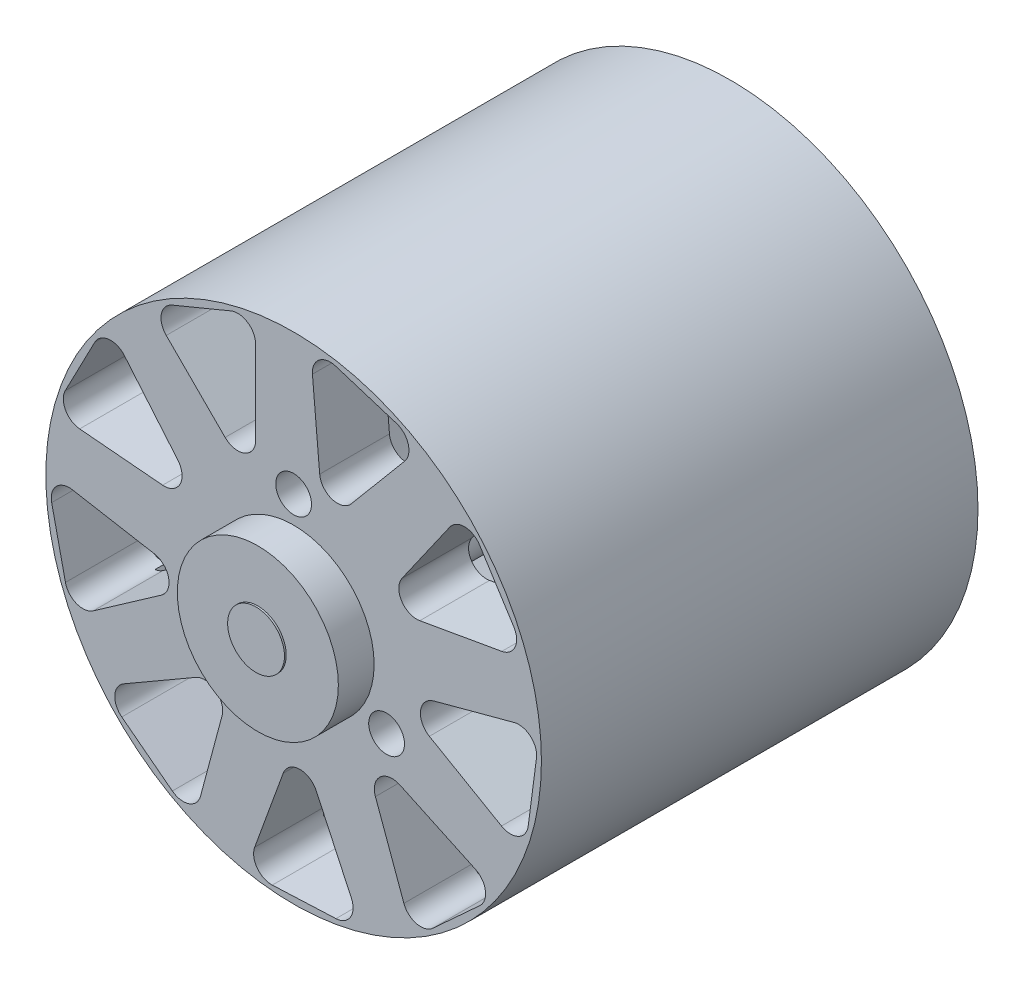
SolidWorks part; units mm, degrees
ref_plane "Front Plane" through (0, 0, 0) normal (0, 0, 1) x (1, 0, 0)
ref_plane "Top Plane" through (0, 0, 0) normal (0, 1, 0) x (1, 0, 0)
ref_plane "Right Plane" through (0, 0, 0) normal (1, 0, 0) x (0, 0, -1)
sketch "Sketch1" plane through (0, 0, 0) normal (0, 0, 1) x (1, 0, 0)
  circle A0 centre (0, 0) radius 13.85
  dimension "D1" = 27.7
extrude "Boss-Extrude1" add sketch "Sketch1" along normal blind 24.4
sketch "Sketch2" plane through (0, 0, 0) normal (0, 0, -1) x (-1, 0, 0)
  circle A0 centre (0, 0) radius 12.85
  dimension "D1" = 25.7
extrude "Cut-Extrude1" cut sketch "Sketch2" against normal blind 20.5
ref_plane "Plane1" through (0, 0, 24.4) normal (0, 0, 1) x (1, 0, 0)
sketch "Sketch3" plane through (0, 0, 24.4) normal (0, 0, 1) x (1, 0, 0)
  line L0 (0, 0) -> (0, 6) construction
  line L1 (0, 0) -> (4.2426, 4.2426) construction
  line L2 (0, 6) -> (4.2426, 4.2426) construction
  line L3 (0, 0) -> (-4.2426, 4.2426) construction
  line L4 (-4.2426, 4.2426) -> (0, 6) construction
  line L5 (1.4565, 7.6917) -> (1.0508, 12.3285)
  line L6 (-2.1213, 7.5355) -> (-2.1213, 12.19)
  line L7 (-3.8284, 6.8284) -> (-7.1196, 10.1196)
  line L8 (-6.7952, 11.7506) -> (-3.504, 13.1139)
  line L9 (2.3477, 13.3693) -> (5.7452, 12.2981)
  line L10 (3.2187, 7.1361) -> (6.2105, 10.7016)
  line L11 (6.0599, 4.956) -> (8.7296, 8.7687)
  line L12 (10.3921, 8.7324) -> (12.3062, 5.728)
  line L13 (7.0527, 3.3976) -> (11.6364, 4.2059)
  line L14 (7.8278, -0.0987) -> (12.3237, 1.106)
  line L15 (13.5739, 0.0095) -> (13.1089, -3.5224)
  line L16 (7.5866, -1.9306) -> (11.6175, -4.2579)
  line L17 (5.933, -5.1072) -> (10.1514, -7.0743)
  line L18 (10.4043, -8.7179) -> (7.7779, -11.1246)
  line L19 (4.5707, -6.3556) -> (6.1626, -10.7293)
  line L20 (1.2621, -7.726) -> (3.2291, -11.9444)
  line L21 (2.3664, -13.366) -> (-1.1925, -13.5214)
  line L22 (-0.5839, -7.8066) -> (-2.1758, -12.1804)
  line L23 (-3.9994, -6.7297) -> (-5.204, -11.2256)
  line L24 (-6.7787, -11.7601) -> (-9.6049, -9.5915)
  line L25 (-5.4653, -5.6049) -> (-9.4962, -7.9321)
  line L26 (-7.3895, -2.5845) -> (-11.2022, -5.2542)
  line L27 (-12.7521, -4.6515) -> (-13.5231, -1.1736)
  line L28 (-7.7894, -0.7806) -> (-12.3731, 0.0277)
  line L29 (-7.322, 2.77) -> (-11.9587, 3.1757)
  line L30 (-12.7586, 4.6336) -> (-11.1136, 7.7935)
  line L31 (-6.4688, 4.409) -> (-9.4606, 7.9745)
  circle A2 centre (0, 6) radius 1
  circle A3 centre (5.1962, -3) radius 1
  circle A4 centre (-5.1962, -3) radius 1
  circle A5 centre (0, 0) radius 13.85 construction
  arc A6 (-3.8284, 6.8284) -> (-2.1213, 7.5355) centre (-3.1213, 7.5355) ccw
  arc A7 (-7.1196, 10.1196) -> (-6.7952, 11.7506) centre (-6.4125, 10.8267) cw
  arc A8 (-2.1213, 12.19) -> (-3.504, 13.1139) centre (-3.1213, 12.19) ccw
  arc A9 (1.0508, 12.3285) -> (2.3477, 13.3693) centre (2.047, 12.4156) cw
  arc A10 (1.4565, 7.6917) -> (3.2187, 7.1361) centre (2.4527, 7.7789) ccw
  arc A11 (6.2105, 10.7016) -> (5.7452, 12.2981) centre (5.4445, 11.3444) ccw
  arc A12 (8.7296, 8.7687) -> (10.3921, 8.7324) centre (9.5487, 8.1951) cw
  arc A13 (6.0599, 4.956) -> (7.0527, 3.3976) centre (6.879, 4.3824) ccw
  arc A14 (11.6364, 4.2059) -> (12.3062, 5.728) centre (11.4628, 5.1907) ccw
  arc A15 (12.3237, 1.106) -> (13.5739, 0.0095) centre (12.5825, 0.14) cw
  arc A16 (7.8278, -0.0987) -> (7.5866, -1.9306) centre (8.0866, -1.0646) ccw
  arc A17 (11.6175, -4.2579) -> (13.1089, -3.5224) centre (12.1175, -3.3918) ccw
  arc A18 (10.1514, -7.0743) -> (10.4043, -8.7179) centre (9.7287, -7.9806) cw
  arc A19 (5.933, -5.1072) -> (4.5707, -6.3556) centre (5.5104, -6.0135) ccw
  arc A20 (6.1626, -10.7293) -> (7.7779, -11.1246) centre (7.1023, -10.3873) ccw
  arc A21 (3.2291, -11.9444) -> (2.3664, -13.366) centre (2.3228, -12.367) cw
  arc A22 (1.2621, -7.726) -> (-0.5839, -7.8066) centre (0.3558, -8.1486) ccw
  arc A23 (-2.1758, -12.1804) -> (-1.1925, -13.5214) centre (-1.2361, -12.5224) ccw
  arc A24 (-5.204, -11.2256) -> (-6.7787, -11.7601) centre (-6.17, -10.9668) cw
  arc A25 (-3.9994, -6.7297) -> (-5.4653, -5.6049) centre (-4.9653, -6.4709) ccw
  arc A26 (-9.4962, -7.9321) -> (-9.6049, -9.5915) centre (-8.9962, -8.7981) ccw
  arc A27 (-11.2022, -5.2542) -> (-12.7521, -4.6515) centre (-11.7758, -4.435) cw
  arc A28 (-7.3895, -2.5845) -> (-7.7894, -0.7806) centre (-7.9631, -1.7654) ccw
  arc A29 (-12.3731, 0.0277) -> (-13.5231, -1.1736) centre (-12.5468, -0.9571) ccw
  arc A30 (-11.9587, 3.1757) -> (-12.7586, 4.6336) centre (-11.8715, 4.1719) cw
  arc A31 (-7.322, 2.77) -> (-6.4688, 4.409) centre (-7.2348, 3.7662) ccw
  arc A32 (-9.4606, 7.9745) -> (-11.1136, 7.7935) centre (-10.2266, 7.3317) ccw
  point P13 (0, 0)
  point P19 (-2.1213, 5.1213)
  point P22 (-8.1779, 11.1779)
  point P25 (-2.1213, 13.6866)
  point P100 (0, 0)
  dimension "D1" = 1
  dimension "D3" = 2
  dimension "D4" = 3
  dimension "D5" = 9
extrude "Cut-Extrude2" cut sketch "Sketch3" against normal blind 4.5
sketch "Sketch4" plane through (0, 0, 24.4) normal (0, 0, 1) x (1, 0, 0)
  circle A0 centre (0, 0) radius 4.5
  dimension "D1" = 9
extrude "Boss-Extrude2" add sketch "Sketch4" along normal blind 2
sketch "Sketch5" plane through (0, 0, 26.4) normal (0, 0, 1) x (1, 0, 0)
  circle A0 centre (0, 0) radius 1.5875
  dimension "D1" = 3.175
extrude "Boss-Extrude3" add sketch "Sketch5" along normal blind 0.1 and the other way blind 35
